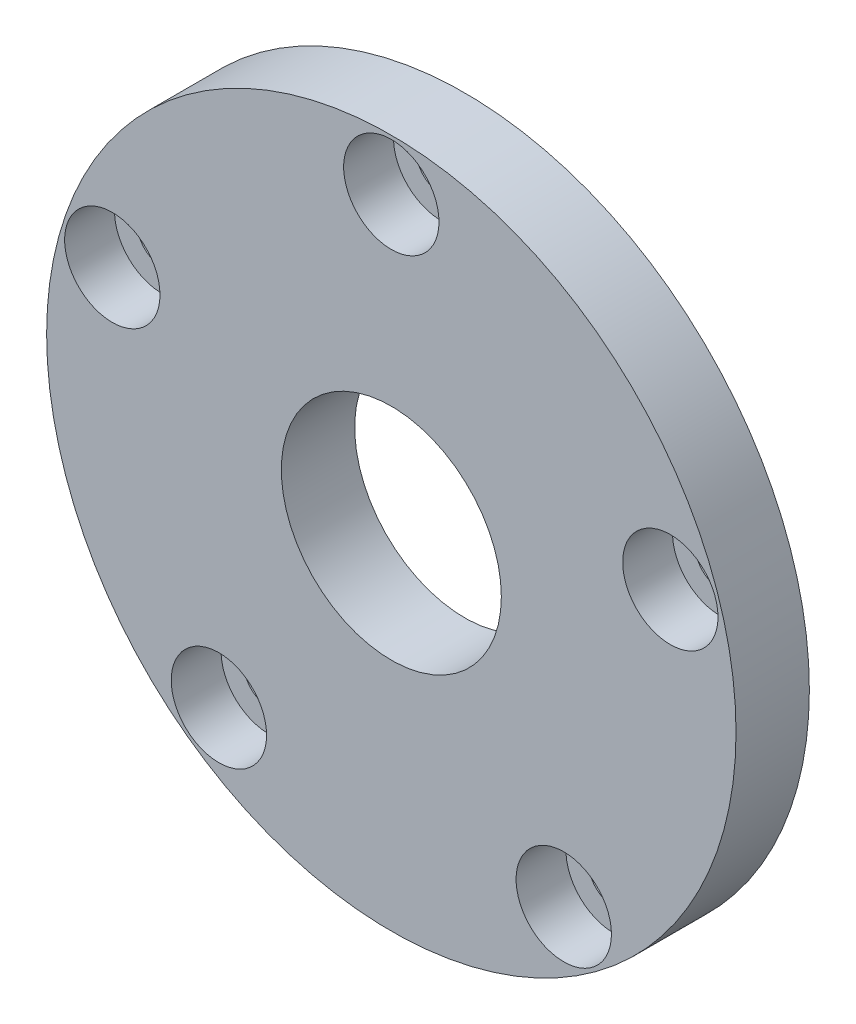
SolidWorks part; units mm, degrees
ref_plane "Front Plane" through (0, 0, 0) normal (0, 0, 1) x (1, 0, 0)
ref_plane "Top Plane" through (0, 0, 0) normal (0, 1, 0) x (1, 0, 0)
ref_plane "Right Plane" through (0, 0, 0) normal (1, 0, 0) x (0, 0, -1)
sketch "Sketch1" plane through (0, 0, 0) normal (0, 0, 1) x (1, 0, 0)
  circle A0 centre (0, 0) radius 23.5
  dimension "D1" = 47
extrude "Boss-Extrude1" add sketch "Sketch1" along normal blind 5
sketch "Sketch5" plane through (0, 0, 5) normal (0, 0, 1) x (1, 0, 0)
  circle A0 centre (0, 0) radius 7.5
  dimension "D1" = 15
extrude "Cut-Extrude1" cut sketch "Sketch5" against normal through all and the other way through all
hole_wizard "CBORE for M3 Hex Socket Head Cap Screw1" positions "Sketch4" profile "Sketch3" counterbore size "M3" standard "ISO"
sketch "Sketch4" plane through (0, 0, 5) normal (0, 0, 1) x (1, 0, 0)
  point P0 (0, 20)
  point P2 (0, 20)
  point P5 (0, 20)
  dimension "D1" = 20
sketch "Sketch3" plane through (0, 20, 5) normal (1, 0, 0) x (0, -1, 0)
  line L0 (0, 0) -> (0, 16.0215)
  line L1 (0, 16.0215) -> (1.7, 15)
  line L2 (1.7, 15) -> (1.7, 3.4)
  line L3 (1.7, 3.4) -> (3.25, 3.4)
  line L4 (3.25, 3.4) -> (3.25, 0)
  line L5 (3.25, 0) -> (0, 0)
  line L10 (0, 16.0215) -> (-1.7, 15) construction
  line L11 (0, -6.35) -> (0, 107.95) construction
  dimension "Hole Dia." = 3.4
  dimension "Hole Depth" = 15
  dimension "C'Bore Dia." = 6.5
  dimension "C'Bore Depth" = 3.4
  dimension "Drill Angle" = 118
pattern_circular "CirPattern1" count 5 over 360 about axis through (0, 0, 0) along (0, 0, 1) of "CBORE for M3 Hex Socket Head Cap Screw1"
equation "\"roller_radius\"= 6.5"
equation "\"eccentricity\"= \"roller_radius\" * 0.325"
equation "\"outer_radius\"= 40"
equation "\"eccentric_shaft_radius\"= 16"
equation "\"rotor_width\"= 10"
equation "\"housing_depth\"= 40"
equation "\"bottom_depth\"= 5"
equation "\"roller_bearing_OD\"= \"roller_radius\" * 2"
equation "\"roller_bearing_ID\"= 6"
equation "\"eccentric_bearing_ID\"= 6"
equation "\"eccentric_bearing_OD\"= 15"
equation "\"roller_bearing_height\"= 5"
equation "\"eccentric_bearing_height\"= 5"
equation "\"bottom_bearing_ID\"= 15"
equation "\"bottom_bearing_OD\"= 32"
equation "\"bottom_bearing_height\"= 9"
equation "\"distance_to_output_rotor_holes\"= 20"
equation "\"D1@Sketch1\"=\"distance_to_output_rotor_holes\"*2+3.5*2"
equation "\"D1@Sketch4\"=\"distance_to_output_rotor_holes\""
equation "\"D1@Sketch5\"=\"bottom_bearing_ID\""
equation "\"D1@Boss-Extrude1\"=\"roller_bearing_height\""
